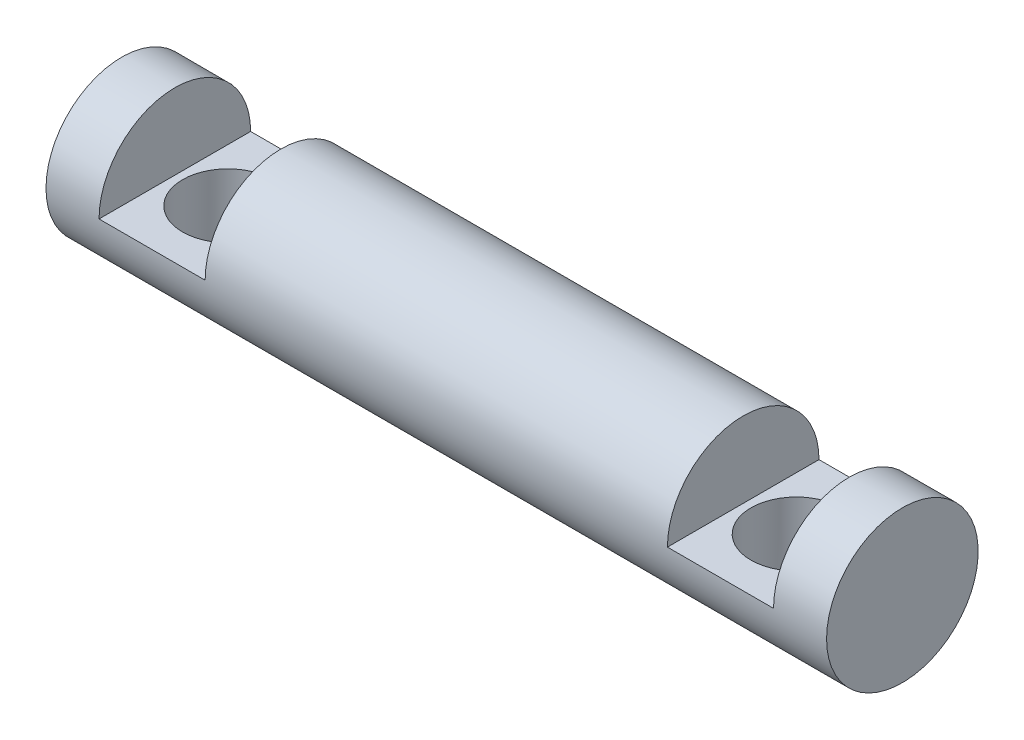
SolidWorks part; units mm, degrees
ref_plane "Front Plane" through (0, 0, 0) normal (0, 0, 1) x (1, 0, 0)
ref_plane "Top Plane" through (0, 0, 0) normal (0, 1, 0) x (1, 0, 0)
ref_plane "Right Plane" through (0, 0, 0) normal (1, 0, 0) x (0, 0, -1)
sketch "Sketch1" plane through (0, 0, 0) normal (0, 0, 1) x (1, 0, 0)
  line L5 (-103, 0) -> (0, 0)
  line L6 (-103, 0) -> (-103, 10)
  line L7 (-103, 10) -> (0, 10)
  line L8 (0, 0) -> (0, 10)
  line L9 (-103, 0) -> (0, 10) construction
  line L10 (-103, 10) -> (0, 0) construction
  point P0 (-51.5, 5)
  dimension "D1" = 103
  dimension "D2" = 10
revolve "Revolve1" add sketch "Sketch1" angle 360 about L5
sketch "Sketch2" plane through (0, 0, 0) normal (1, 0, 0) x (0, 0, -1)
  line L0 (-10.8723, 5) -> (10.8723, 5)
  arc A3 (10.8723, 5) -> (-10.8723, 5) centre (0, 0) ccw
  dimension "D1" = 5
extrude "Cut-Extrude1" cut sketch "Sketch2" against normal blind 14 from offset 7 contours A3 L0 offset against normal yes
sketch "Sketch3" plane through (-103, 0, 0) normal (-1, 0, 0) x (0, 0, 1)
  line L1 (-13.4316, 5) -> (13.4316, 5)
  arc A0 (13.4316, 5) -> (-13.4316, 5) centre (0, 0) ccw
  dimension "D1" = 5
extrude "Cut-Extrude2" cut sketch "Sketch3" against normal blind 14 from offset 7 offset against normal yes
sketch "Sketch4" plane through (0, 0, 0) normal (0, 1, 0) x (1, 0, 0)
  circle A0 centre (-89, 0) radius 5.983
  circle A1 centre (-14, 0) radius 5.983
  dimension "D1" = 11.966
  dimension "D2" = 11.966
  dimension "D3" = 75
extrude "Cut-Extrude3" cut sketch "Sketch4" against normal through all both and the other way through all
sketch "Sketch5" plane through (0, 5, 0) normal (0, 1, 0) x (1, 0, 0)
  line L0 (-51.5, -17.8279) -> (-51.5, 26.5298) construction
  line L1 (-96, -12.7135) -> (-82, -12.7135)
  line L2 (-96, -12.7135) -> (-96, 12.7135)
  line L3 (-96, 12.7135) -> (-82, 12.7135)
  line L4 (-82, -12.7135) -> (-82, 12.7135)
  line L5 (-96, -12.7135) -> (-82, 12.7135) construction
  line L6 (-96, 12.7135) -> (-82, -12.7135) construction
  line L8 (-7, 12.7135) -> (-21, -12.7135) construction
  line L9 (-7, -12.7135) -> (-21, 12.7135) construction
  line L10 (-21, -12.7135) -> (-21, 12.7135)
  line L11 (-7, 12.7135) -> (-21, 12.7135)
  line L12 (-7, -12.7135) -> (-7, 12.7135)
  line L13 (-7, -12.7135) -> (-21, -12.7135)
  point P0 (-89, 0)
  point P14 (-14, 0)
  dimension "D1" = 14
extrude "Cut-Extrude4" cut sketch "Sketch5" against normal blind 5
